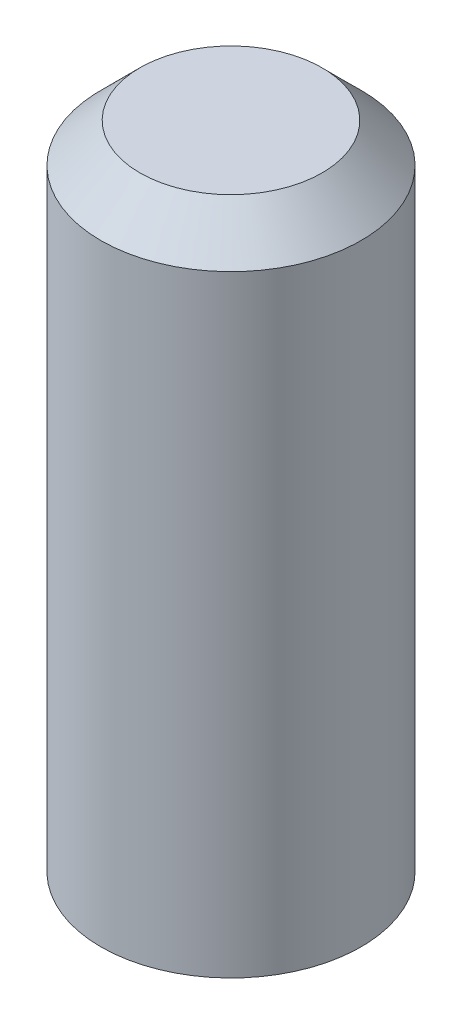
SolidWorks part; units mm, degrees
ref_plane "Front" through (0, 0, 0) normal (0, 0, 1) x (1, 0, 0)
ref_plane "Top" through (0, 0, 0) normal (0, 1, 0) x (1, 0, 0)
ref_plane "Right" through (0, 0, 0) normal (1, 0, 0) x (0, 0, -1)
sketch "Эскиз1" plane through (0, 0, 0) normal (0, 1, 0) x (1, 0, 0)
  circle A0 centre (0, 0) radius 2
  dimension "D1" = 4
extrude "Бобышка-Вытянуть1" add sketch "Эскиз1" along normal blind 10
chamfer "Фаска1" distance 0.6 angle 45 1 edges at (0, 10, 2)
